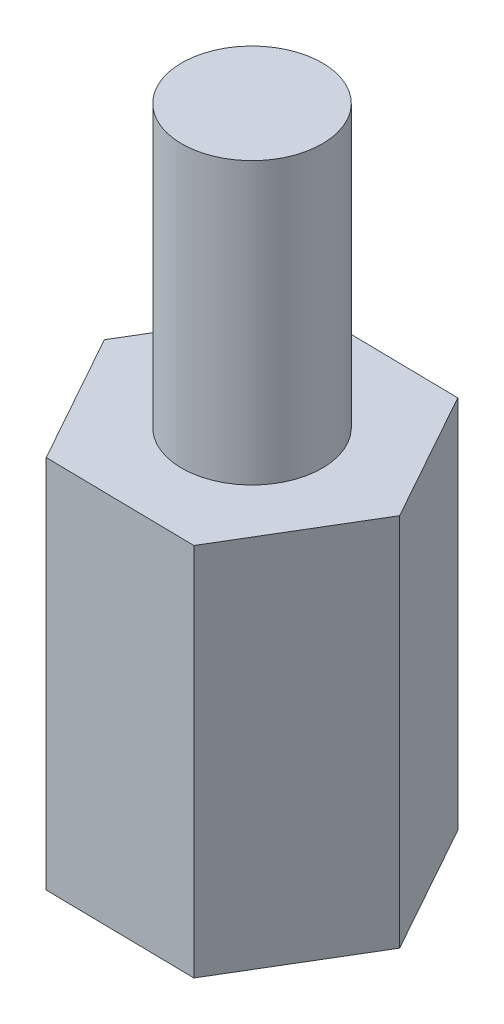
SolidWorks part; units mm, degrees
ref_plane "前视基准面" through (0, 0, 0) normal (0, 0, 1) x (1, 0, 0)
ref_plane "上视基准面" through (0, 0, 0) normal (0, 1, 0) x (1, 0, 0)
ref_plane "右视基准面" through (0, 0, 0) normal (1, 0, 0) x (0, 0, -1)
sketch "草图1" plane through (0, 0, 0) normal (0, 1, 0) x (1, 0, 0)
  line L1 (-2.2187, -2.3508) -> (-0.5732, 0.3987)
  line L2 (-0.5732, 0.3987) -> (-2.1316, 3.1985)
  line L3 (-2.1316, 3.1985) -> (-5.3355, 3.2488)
  line L4 (-5.3355, 3.2488) -> (-6.981, 0.4993)
  line L5 (-6.981, 0.4993) -> (-5.4226, -2.3005)
  line L6 (-5.4226, -2.3005) -> (-2.2187, -2.3508)
  circle A0 centre (-3.7771, 0.449) radius 2.775 construction
  circle A1 centre (-3.7771, 0.449) radius 1.5
  dimension "D1" = 5.55
extrude "凸台-拉伸1" add sketch "草图1" along normal blind 8
sketch "草图2" plane through (0, 8, 0) normal (0, 1, 0) x (1, 0, 0)
  circle A0 centre (-3.7771, 0.449) radius 1.5
extrude "凸台-拉伸2" add sketch "草图2" along normal blind 6 separate body
